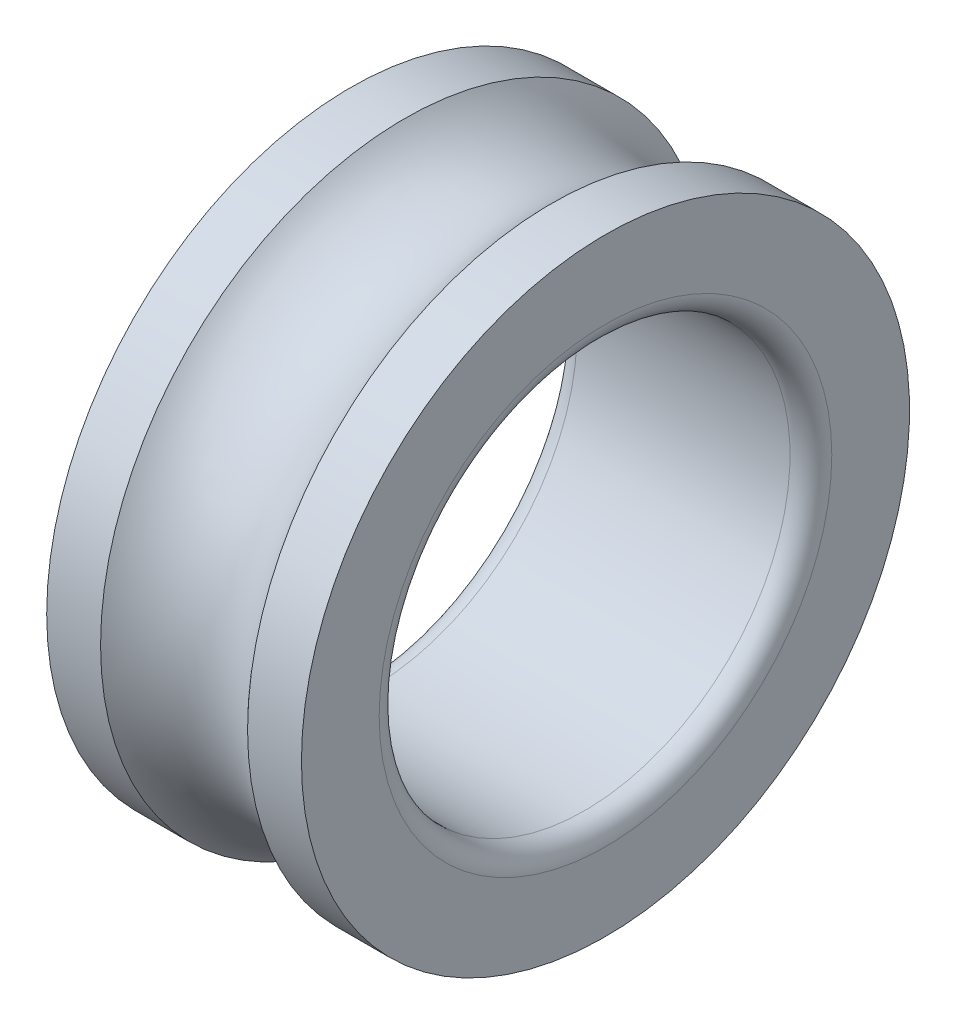
SolidWorks part; units mm, degrees
ref_plane "Front Plane" through (0, 0, 0) normal (0, 0, 1) x (1, 0, 0)
ref_plane "Top Plane" through (0, 0, 0) normal (0, 1, 0) x (1, 0, 0)
ref_plane "Right Plane" through (0, 0, 0) normal (1, 0, 0) x (0, 0, -1)
sketch "Sketch1" plane through (0, 0, 0) normal (0, 0, 1) x (1, 0, 0)
  line L0 (-21.6667, 0) -> (44, 0) construction
  line L1 (0, 25) -> (0, 0) construction
  line L2 (-15.5, 37) -> (-8.9443, 37)
  line L3 (-15.5, 37) -> (-15.5, 27.54)
  line L4 (-12.96, 25) -> (12.96, 25)
  line L5 (15.5, 37) -> (15.5, 27.54)
  line L6 (-15.5, 37) -> (15.5, 25) construction
  line L7 (-15.5, 25) -> (15.5, 37) construction
  line L8 (8.9443, 37) -> (15.5, 37)
  arc A0 (8.9443, 37) -> (-8.9443, 37) centre (0, 45) cw
  arc A1 (-15.5, 27.54) -> (-12.96, 25) centre (-12.96, 27.54) ccw
  arc A2 (12.96, 25) -> (15.5, 27.54) centre (12.96, 27.54) ccw
  point P3 (0, 31)
  dimension "D5" = 12
  dimension "D6" = 2.54
  dimension "D1" = 31
  dimension "D2" = 25
  dimension "D3" = 37
  dimension "D4" = 8
revolve "Revolve1" add sketch "Sketch1" angle 360 about L0
scale "Scale1" scale about centroid uniform scaling yes scale factor 1.413611
